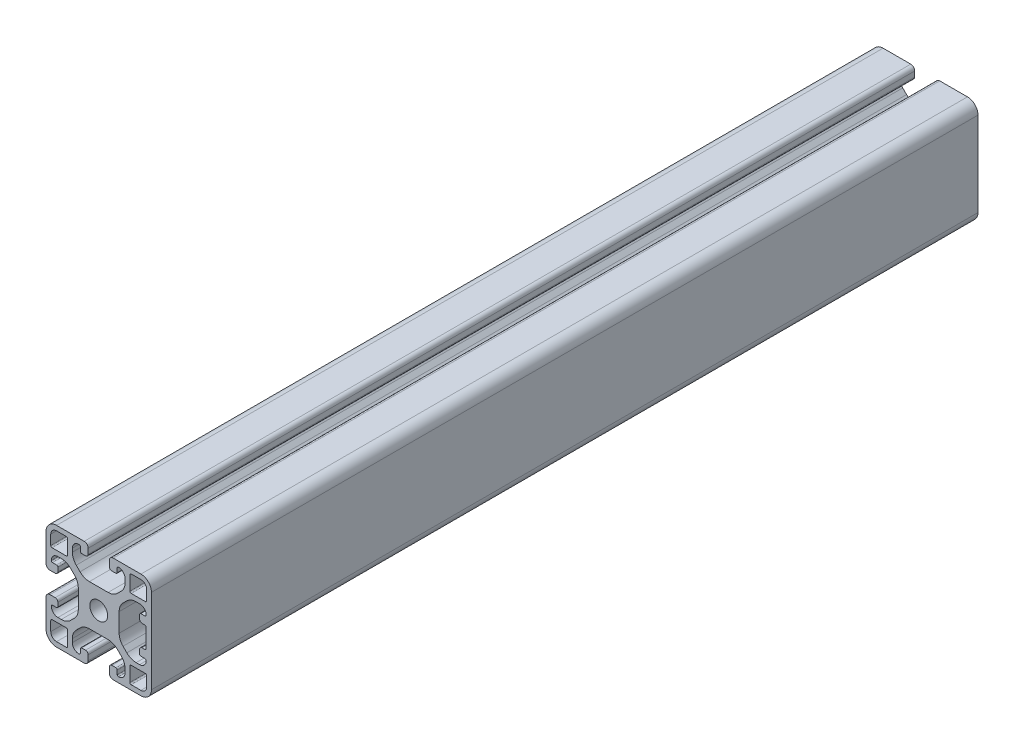
SolidWorks part; units mm, degrees
ref_plane "Piano frontale" through (0, 0, 0) normal (0, 0, 1) x (1, 0, 0)
ref_plane "Piano superiore" through (0, 0, 0) normal (0, 1, 0) x (1, 0, 0)
ref_plane "Piano destro" through (0, 0, 0) normal (1, 0, 0) x (0, 0, -1)
ref_plane "Piano1" through (0, 0, -340) normal (0, 0, -1) x (-1, 0, 0)
sketch "Schizzo1" plane through (0, 0, -340) normal (0, 0, -1) x (-1, 0, 0)
  line L0 (-12.3, -18.2) -> (-16, -18.2)
  line L1 (-18.2, -16) -> (-18.2, -12.3)
  line L2 (-17.7, -11.8) -> (-12.3, -11.8)
  line L3 (-11.8, -12.3) -> (-11.8, -17.7)
  line L4 (-11.8, 17.7) -> (-11.8, 12.3)
  line L5 (-12.3, 11.8) -> (-17.7, 11.8)
  line L6 (-18.2, 12.3) -> (-18.2, 16)
  line L7 (-16, 18.2) -> (-12.3, 18.2)
  line L8 (18.2, 16) -> (18.2, 12.3)
  line L9 (17.7, 11.8) -> (12.3, 11.8)
  line L10 (11.8, 12.3) -> (11.8, 17.7)
  line L11 (12.3, 18.2) -> (16, 18.2)
  line L12 (6.5, -15.5) -> (5, -15.5)
  line L13 (4, -16.5) -> (4, -18.5)
  line L14 (5.5, -20) -> (16, -20)
  line L15 (20, -16) -> (20, -5.5)
  line L16 (18.5, -4) -> (16.5, -4)
  line L17 (15.5, -5) -> (15.5, -6.5)
  line L18 (16, -7) -> (17.55, -7)
  line L19 (18, -7.45) -> (18, -7.5)
  line L20 (15.5, -10) -> (14.1924, -10)
  line L21 (10.6569, -8.5355) -> (9.2145, -7.0931)
  line L22 (7.75, -3.5576) -> (7.75, 3.5576)
  line L23 (9.2145, 7.0931) -> (10.6569, 8.5355)
  line L24 (14.1924, 10) -> (15.5, 10)
  line L25 (18, 7.5) -> (18, 7.45)
  line L26 (17.55, 7) -> (16, 7)
  line L27 (15.5, 6.5) -> (15.5, 5)
  line L28 (16.5, 4) -> (18.5, 4)
  line L29 (20, 5.5) -> (20, 16)
  line L30 (16, 20) -> (5.5, 20)
  line L31 (4, 18.5) -> (4, 16.5)
  line L32 (5, 15.5) -> (6.5, 15.5)
  line L33 (7, 16) -> (7, 17.55)
  line L34 (7.45, 18) -> (7.5, 18)
  line L35 (10, 15.5) -> (10, 14.1924)
  line L36 (8.5355, 10.6569) -> (7.0931, 9.2145)
  line L37 (3.5576, 7.75) -> (-3.5576, 7.75)
  line L38 (-7.0931, 9.2145) -> (-8.5355, 10.6569)
  line L39 (-10, 14.1924) -> (-10, 15.5)
  line L40 (-7.5, 18) -> (-7.45, 18)
  line L41 (-7, 17.55) -> (-7, 16)
  line L42 (-6.5, 15.5) -> (-5, 15.5)
  line L43 (-4, 16.5) -> (-4, 18.5)
  line L44 (-5.5, 20) -> (-16, 20)
  line L45 (-20, 16) -> (-20, -16)
  line L46 (-16, -20) -> (-5.5, -20)
  line L47 (-4, -18.5) -> (-4, -16.5)
  line L48 (-5, -15.5) -> (-6.5, -15.5)
  line L49 (-7, -16) -> (-7, -17.55)
  line L50 (-7.45, -18) -> (-7.5, -18)
  line L51 (-10, -15.5) -> (-10, -14.1924)
  line L52 (-8.5355, -10.6569) -> (-7.0931, -9.2145)
  line L53 (-3.5576, -7.75) -> (3.5576, -7.75)
  line L54 (7.0931, -9.2145) -> (8.5355, -10.6569)
  line L55 (10, -14.1924) -> (10, -15.5)
  line L56 (7.5, -18) -> (7.45, -18)
  line L57 (7, -17.55) -> (7, -16)
  line L58 (18.2, -12.3) -> (18.2, -16)
  line L59 (16, -18.2) -> (12.3, -18.2)
  line L60 (11.8, -17.7) -> (11.8, -12.3)
  line L61 (12.3, -11.8) -> (17.7, -11.8)
  line L62 (-16, 7) -> (-17.5, 7)
  line L63 (-15.5, 10) -> (-14.1924, 10)
  line L64 (-10.6569, 8.5355) -> (-9.2145, 7.0931)
  line L65 (-7.75, 3.5576) -> (-7.75, -3.5576)
  line L66 (-9.2145, -7.0931) -> (-10.6569, -8.5355)
  line L67 (-14.1924, -10) -> (-15.5, -10)
  line L68 (-17.5, -7) -> (-16, -7)
  line L69 (-15.5, -6.5) -> (-15.5, -5)
  line L70 (-16.5, -4) -> (-17.5, -4)
  line L71 (-18, -3.5) -> (-18, 3.5)
  line L72 (-17.5, 4) -> (-16.5, 4)
  line L73 (-15.5, 5) -> (-15.5, 6.5)
  arc A0 (-16, -18.2) -> (-18.2, -16) centre (-16, -16) cw
  arc A1 (-18.2, -12.3) -> (-17.7, -11.8) centre (-17.7, -12.3) cw
  arc A2 (-12.3, -11.8) -> (-11.8, -12.3) centre (-12.3, -12.3) cw
  arc A3 (-11.8, -17.7) -> (-12.3, -18.2) centre (-12.3, -17.7) cw
  arc A4 (-12.3, 18.2) -> (-11.8, 17.7) centre (-12.3, 17.7) cw
  arc A5 (-11.8, 12.3) -> (-12.3, 11.8) centre (-12.3, 12.3) cw
  arc A6 (-17.7, 11.8) -> (-18.2, 12.3) centre (-17.7, 12.3) cw
  arc A7 (-18.2, 16) -> (-16, 18.2) centre (-16, 16) cw
  arc A8 (16, 18.2) -> (18.2, 16) centre (16, 16) cw
  arc A9 (18.2, 12.3) -> (17.7, 11.8) centre (17.7, 12.3) cw
  arc A10 (12.3, 11.8) -> (11.8, 12.3) centre (12.3, 12.3) cw
  arc A11 (11.8, 17.7) -> (12.3, 18.2) centre (12.3, 17.7) cw
  arc A12 (5, -15.5) -> (4, -16.5) centre (5, -16.5) ccw
  arc A13 (4, -18.5) -> (5.5, -20) centre (5.5, -18.5) ccw
  arc A14 (16, -20) -> (20, -16) centre (16, -16) ccw
  arc A15 (20, -5.5) -> (18.5, -4) centre (18.5, -5.5) ccw
  arc A16 (16.5, -4) -> (15.5, -5) centre (16.5, -5) ccw
  arc A17 (15.5, -6.5) -> (16, -7) centre (16, -6.5) ccw
  arc A18 (17.55, -7) -> (18, -7.45) centre (17.55, -7.45) cw
  arc A19 (18, -7.5) -> (15.5, -10) centre (15.5, -7.5) cw
  arc A20 (14.1924, -10) -> (10.6569, -8.5355) centre (14.1924, -5) cw
  arc A21 (9.2145, -7.0931) -> (7.75, -3.5576) centre (12.75, -3.5576) cw
  arc A22 (7.75, 3.5576) -> (9.2145, 7.0931) centre (12.75, 3.5576) cw
  arc A23 (10.6569, 8.5355) -> (14.1924, 10) centre (14.1924, 5) cw
  arc A24 (15.5, 10) -> (18, 7.5) centre (15.5, 7.5) cw
  arc A25 (18, 7.45) -> (17.55, 7) centre (17.55, 7.45) cw
  arc A26 (16, 7) -> (15.5, 6.5) centre (16, 6.5) ccw
  arc A27 (15.5, 5) -> (16.5, 4) centre (16.5, 5) ccw
  arc A28 (18.5, 4) -> (20, 5.5) centre (18.5, 5.5) ccw
  arc A29 (20, 16) -> (16, 20) centre (16, 16) ccw
  arc A30 (5.5, 20) -> (4, 18.5) centre (5.5, 18.5) ccw
  arc A31 (4, 16.5) -> (5, 15.5) centre (5, 16.5) ccw
  arc A32 (6.5, 15.5) -> (7, 16) centre (6.5, 16) ccw
  arc A33 (7, 17.55) -> (7.45, 18) centre (7.45, 17.55) cw
  arc A34 (7.5, 18) -> (10, 15.5) centre (7.5, 15.5) cw
  arc A35 (10, 14.1924) -> (8.5355, 10.6569) centre (5, 14.1924) cw
  arc A36 (7.0931, 9.2145) -> (3.5576, 7.75) centre (3.5576, 12.75) cw
  arc A37 (-3.5576, 7.75) -> (-7.0931, 9.2145) centre (-3.5576, 12.75) cw
  arc A38 (-8.5355, 10.6569) -> (-10, 14.1924) centre (-5, 14.1924) cw
  arc A39 (-10, 15.5) -> (-7.5, 18) centre (-7.5, 15.5) cw
  arc A40 (-7.45, 18) -> (-7, 17.55) centre (-7.45, 17.55) cw
  arc A41 (-7, 16) -> (-6.5, 15.5) centre (-6.5, 16) ccw
  arc A42 (-5, 15.5) -> (-4, 16.5) centre (-5, 16.5) ccw
  arc A43 (-4, 18.5) -> (-5.5, 20) centre (-5.5, 18.5) ccw
  arc A44 (-16, 20) -> (-20, 16) centre (-16, 16) ccw
  arc A45 (-20, -16) -> (-16, -20) centre (-16, -16) ccw
  arc A46 (-5.5, -20) -> (-4, -18.5) centre (-5.5, -18.5) ccw
  arc A47 (-4, -16.5) -> (-5, -15.5) centre (-5, -16.5) ccw
  arc A48 (-6.5, -15.5) -> (-7, -16) centre (-6.5, -16) ccw
  arc A49 (-7, -17.55) -> (-7.45, -18) centre (-7.45, -17.55) cw
  arc A50 (-7.5, -18) -> (-10, -15.5) centre (-7.5, -15.5) cw
  arc A51 (-10, -14.1924) -> (-8.5355, -10.6569) centre (-5, -14.1924) cw
  arc A52 (-7.0931, -9.2145) -> (-3.5576, -7.75) centre (-3.5576, -12.75) cw
  arc A53 (3.5576, -7.75) -> (7.0931, -9.2145) centre (3.5576, -12.75) cw
  arc A54 (8.5355, -10.6569) -> (10, -14.1924) centre (5, -14.1924) cw
  arc A55 (10, -15.5) -> (7.5, -18) centre (7.5, -15.5) cw
  arc A56 (7.45, -18) -> (7, -17.55) centre (7.45, -17.55) cw
  arc A57 (7, -16) -> (6.5, -15.5) centre (6.5, -16) ccw
  arc A58 (17.7, -11.8) -> (18.2, -12.3) centre (17.7, -12.3) cw
  arc A59 (18.2, -16) -> (16, -18.2) centre (16, -16) cw
  arc A60 (12.3, -18.2) -> (11.8, -17.7) centre (12.3, -17.7) cw
  arc A61 (11.8, -12.3) -> (12.3, -11.8) centre (12.3, -12.3) cw
  circle A62 centre (0, 0) radius 3.4
  arc A63 (-15.5, 6.5) -> (-16, 7) centre (-16, 6.5) ccw
  arc A64 (-17.5, 7) -> (-18, 7.5) centre (-17.5, 7.5) cw
  arc A65 (-18, 7.5) -> (-15.5, 10) centre (-15.5, 7.5) cw
  arc A66 (-14.1924, 10) -> (-10.6569, 8.5355) centre (-14.1924, 5) cw
  arc A67 (-9.2145, 7.0931) -> (-7.75, 3.5576) centre (-12.75, 3.5576) cw
  arc A68 (-7.75, -3.5576) -> (-9.2145, -7.0931) centre (-12.75, -3.5576) cw
  arc A69 (-10.6569, -8.5355) -> (-14.1924, -10) centre (-14.1924, -5) cw
  arc A70 (-15.5, -10) -> (-18, -7.5) centre (-15.5, -7.5) cw
  arc A71 (-18, -7.5) -> (-17.5, -7) centre (-17.5, -7.5) cw
  arc A72 (-16, -7) -> (-15.5, -6.5) centre (-16, -6.5) ccw
  arc A73 (-15.5, -5) -> (-16.5, -4) centre (-16.5, -5) ccw
  arc A74 (-17.5, -4) -> (-18, -3.5) centre (-17.5, -3.5) cw
  arc A75 (-18, 3.5) -> (-17.5, 4) centre (-17.5, 3.5) cw
  arc A76 (-16.5, 4) -> (-15.5, 5) centre (-16.5, 5) ccw
extrude "Estrusione-Estrusione1" add sketch "Schizzo1" against normal blind 313.48
